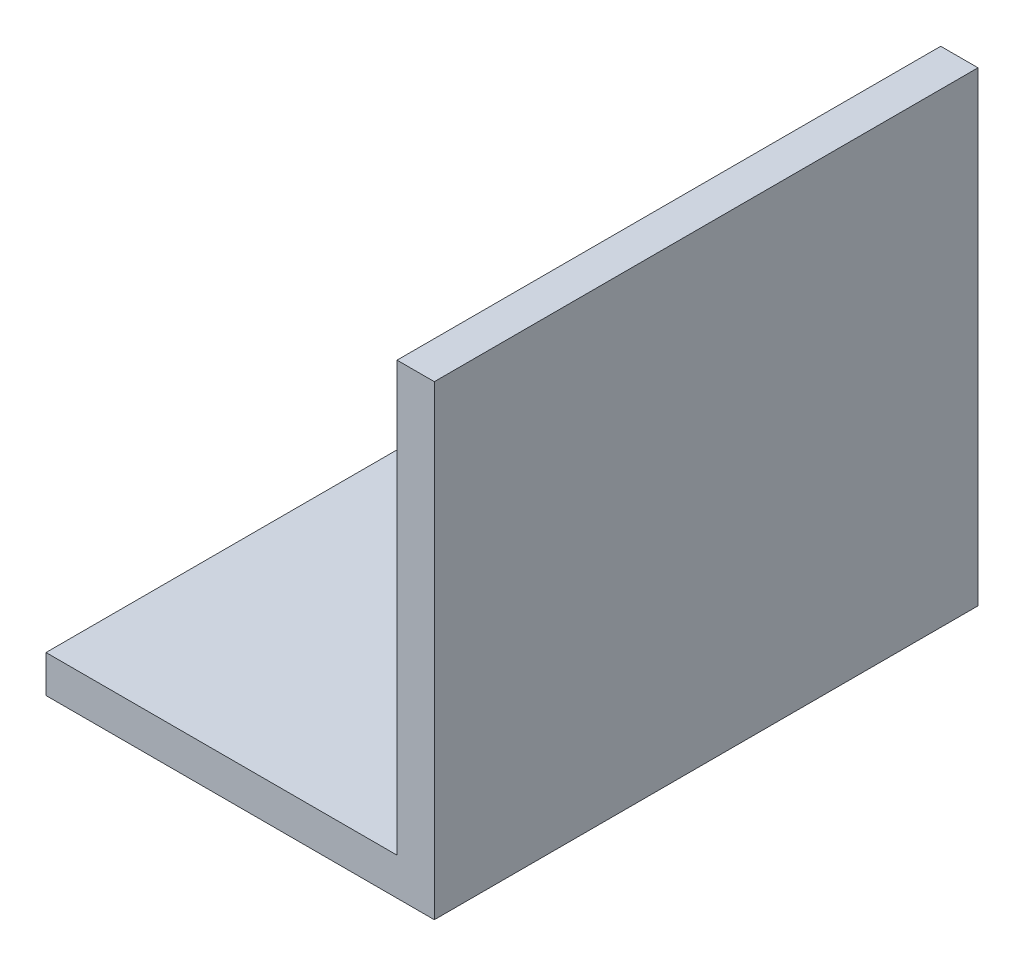
SolidWorks part; units mm, degrees
ref_plane "Front Plane" through (0, 0, 0) normal (0, 0, 1) x (1, 0, 0)
ref_plane "Top Plane" through (0, 0, 0) normal (0, 1, 0) x (1, 0, 0)
ref_plane "Right Plane" through (0, 0, 0) normal (1, 0, 0) x (0, 0, -1)
sketch "Sketch1" plane through (0, 0, 0) normal (0, 0, 1) x (1, 0, 0)
  line L0 (-14.351, 0) -> (0, 0)
  line L2 (-14.351, 0) -> (-14.351, -1.524)
  line L3 (-14.351, -1.524) -> (1.524, -1.524)
  line L6 (1.524, -1.524) -> (1.524, 17.526)
  line L7 (1.524, 17.526) -> (0, 17.526)
  line L8 (0, 0) -> (0, 17.526)
  dimension "D2" = 1.524
  dimension "D3" = 15.875
  dimension "D4" = 19.05
extrude "Boss-Extrude1" add sketch "Sketch1" along normal mid plane 22.225
hole_wizard "#8 Clearance Hole1" positions "Sketch4" profile "Sketch3" hole size "#8" standard "ANSI Inch"
sketch "Sketch4" plane through (0, 0, 0) normal (0, 1, 0) x (1, 0, 0)
  line L0 (-7.1755, 11.1125) -> (-7.1755, -11.1125) construction
  line L1 (0, 11.1125) -> (-14.351, 11.1125) construction
  line L2 (0, -11.1125) -> (-14.351, -11.1125) construction
  line L4 (0, 0) -> (-14.351, 0) construction
  line L5 (-14.351, -11.1125) -> (-14.351, 11.1125) construction
  point P0 (-7.1755, 0)
sketch "Sketch3" plane through (-7.1755, 0, 0) normal (1, 0, 0) x (0, 0, 1)
  line L0 (0, 0) -> (0, 33.1007)
  line L1 (0, 33.1007) -> (2.2479, 31.75)
  line L2 (2.2479, 31.75) -> (2.2479, 0)
  line L5 (2.2479, 0) -> (0, 0)
  line L10 (0, 33.1007) -> (-2.2479, 31.75) construction
  line L11 (0, -6.35) -> (0, 107.95) construction
  dimension "Hole Dia." = 4.4958
  dimension "Hole Depth" = 31.75
  dimension "Drill Angle" = 118
